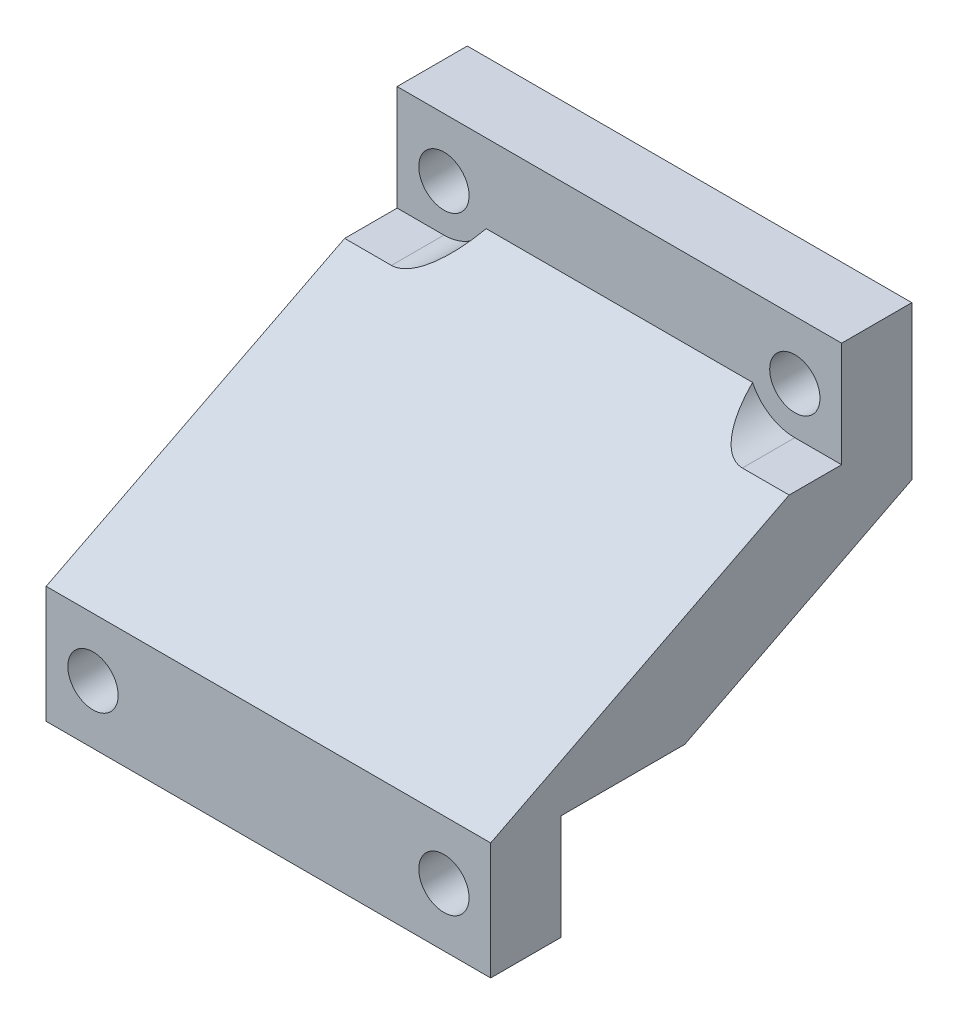
SolidWorks part; units mm, degrees
ref_plane "Front Plane" through (0, 0, 0) normal (0, 0, 1) x (1, 0, 0)
ref_plane "Top Plane" through (0, 0, 0) normal (0, 1, 0) x (1, 0, 0)
ref_plane "Right Plane" through (0, 0, 0) normal (1, 0, 0) x (0, 0, -1)
sketch "Sketch2" plane through (0, 0, 0) normal (1, 0, 0) x (0, 0, -1)
  line L0 (0, 76.4896) -> (0, -64.9621) construction
  line L1 (0, 0) -> (6, 0)
  line L2 (6, 0) -> (6, 3.6)
  line L3 (6, 3.6) -> (36, 18.8858)
  line L4 (36, 18.8858) -> (36, 32)
  line L5 (36, 32) -> (30, 32)
  line L6 (30, 32) -> (30, 25.2858)
  line L7 (30, 25.2858) -> (0, 10)
  line L8 (0, 0) -> (0, 10)
  dimension "D1" = 6
  dimension "D2" = 3.6
  dimension "D3" = 27
  dimension "D4" = 36
  dimension "D5" = 32
  dimension "D6" = 10
  dimension "D7" = 6
extrude "Boss-Extrude1" add sketch "Sketch2" along normal mid plane 38 contours L3 L4 L5 L6 L7 L8 L1 L2
sketch "Sketch5" plane through (0, 0, -30) normal (0, 0, 1) x (1, 0, 0)
  line L0 (0, 43.2862) -> (0, -11.0033) construction
  line L1 (19, 32) -> (-19, 32) construction
  circle A0 centre (-15, 27) radius 2.15
  circle A1 centre (15, 27) radius 2.15
  dimension "D1" = 4.3
  dimension "D2" = 15
  dimension "D3" = 5
extrude "Cut-Extrude1" cut sketch "Sketch5" against normal through all both and the other way through all
sketch "Sketch6" plane through (0, 0, 0) normal (0, 0, 1) x (1, 0, 0)
  line L0 (0, 13.8064) -> (0, -4.4311) construction
  line L1 (19, 0) -> (-19, 0) construction
  circle A0 centre (-15, 5) radius 2.15
  circle A1 centre (15, 5) radius 2.15
  dimension "D1" = 4.3
  dimension "D2" = 5
  dimension "D3" = 15
extrude "Cut-Extrude2" cut sketch "Sketch6" against normal up to surface (6 mm away) up to face at (0, 1.8, -6)
sketch "Sketch9" plane through (0, 0, -6) normal (0, 0, -1) x (-1, 0, 0)
  line L0 (0, 38.005) -> (0, -9.5207) construction
  line L1 (-19, 0) -> (-19, 9)
  line L2 (-19, 3.6) -> (-19, 18.8858) construction
  line L3 (-19, 9) -> (-15, 9)
  line L4 (-11, 5) -> (-11, 0)
  line L5 (-19, 0) -> (19, 0) construction
  line L6 (-11, 0) -> (-19, 0)
  line L7 (19, 0) -> (19, 9)
  line L8 (19, 9) -> (15, 9)
  line L9 (11, 5) -> (11, 0)
  line L10 (11, 0) -> (19, 0)
  arc A0 (-15, 9) -> (-11, 5) centre (-15, 5) cw
  arc A1 (15, 9) -> (11, 5) centre (15, 5) ccw
  dimension "D3" = 4
  dimension "D1" = 11
  dimension "D2" = 9
extrude "Cut-Extrude6" cut sketch "Sketch9" along normal through all
sketch "Sketch11" plane through (0, 0, -30) normal (0, 0, 1) x (1, 0, 0)
  line L0 (0, 38.7983) -> (0, -2.0659) construction
  line L1 (11, 32) -> (19, 32)
  line L2 (19, 32) -> (-19, 32) construction
  line L3 (19, 32) -> (19, 23)
  line L4 (19, 25.2858) -> (19, 10) construction
  line L5 (19, 23) -> (15, 23)
  line L6 (11, 27) -> (11, 32)
  line L7 (-19, 23) -> (-15, 23)
  line L8 (-19, 32) -> (-19, 23)
  line L9 (-11, 32) -> (-19, 32)
  line L10 (-11, 27) -> (-11, 32)
  arc A0 (11, 27) -> (15, 23) centre (15, 27) ccw
  arc A1 (-11, 27) -> (-15, 23) centre (-15, 27) cw
  dimension "D3" = 4
  dimension "D1" = 11
  dimension "D2" = 9
extrude "Cut-Extrude7" cut sketch "Sketch11" along normal blind 36 contours L10 L9 L8 L7 A1 | L6 L1 L3 L5 A0
